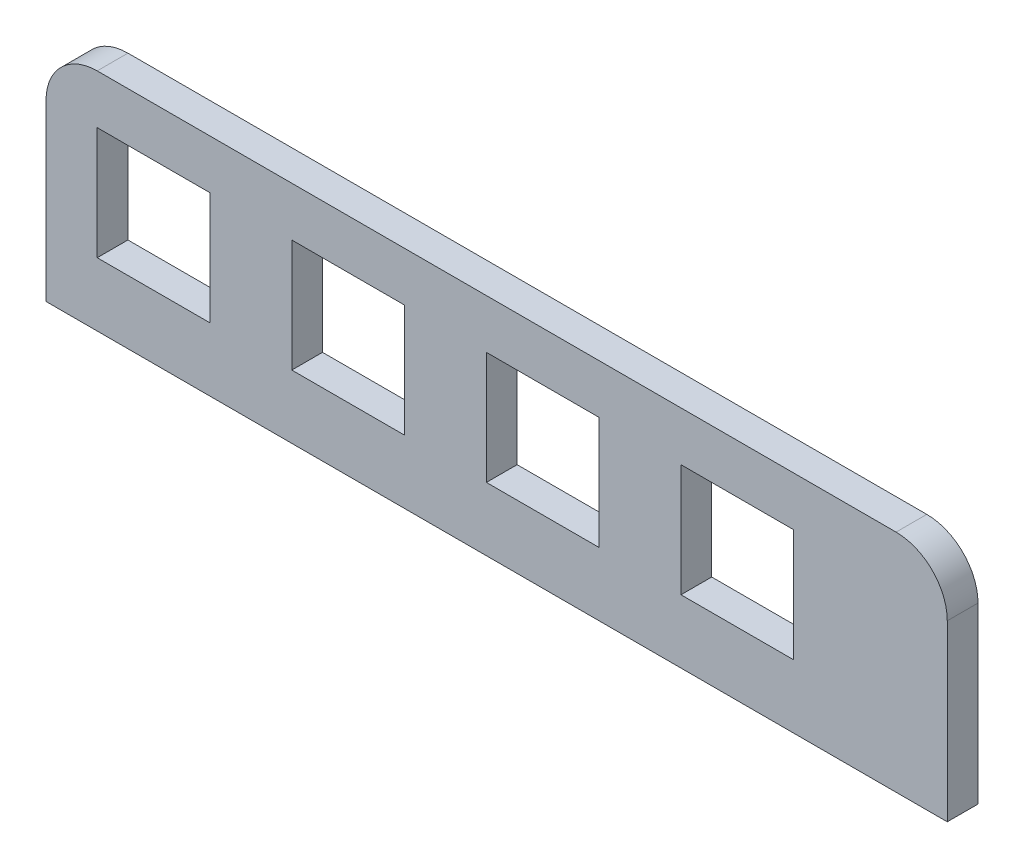
SolidWorks part; units mm, degrees
ref_plane "Front Plane" through (0, 0, 0) normal (0, 0, 1) x (1, 0, 0)
ref_plane "Top Plane" through (0, 0, 0) normal (0, 1, 0) x (1, 0, 0)
ref_plane "Right Plane" through (0, 0, 0) normal (1, 0, 0) x (0, 0, -1)
sketch "Sketch1" plane through (0, 0, 0) normal (0, 0, 1) x (1, 0, 0)
  line L0 (16, 17.2) -> (16, 22) construction
  line L1 (0, 0) -> (88, 0)
  line L2 (0, 0) -> (0, 17)
  line L3 (5, 22) -> (83, 22)
  line L4 (88, 0) -> (88, 17)
  line L5 (5, 6.2) -> (16, 6.2)
  line L6 (5, 6.2) -> (5, 17.2)
  line L7 (5, 17.2) -> (16, 17.2)
  line L8 (16, 6.2) -> (16, 17.2)
  line L10 (16, 6.2) -> (24, 6.2) construction
  line L11 (24, 6.2) -> (35, 6.2)
  line L12 (24, 6.2) -> (24, 17.2)
  line L13 (24, 17.2) -> (35, 17.2)
  line L14 (35, 6.2) -> (35, 17.2)
  line L15 (43, 6.2) -> (54, 6.2)
  line L16 (43, 6.2) -> (43, 17.2)
  line L17 (43, 17.2) -> (54, 17.2)
  line L18 (54, 6.2) -> (54, 17.2)
  line L19 (62, 6.2) -> (73, 6.2)
  line L20 (62, 6.2) -> (62, 17.2)
  line L21 (62, 17.2) -> (73, 17.2)
  line L22 (73, 6.2) -> (73, 17.2)
  line L23 (35, 6.2) -> (43, 6.2) construction
  line L24 (54, 6.2) -> (62, 6.2) construction
  arc A0 (0, 17) -> (5, 22) centre (5, 17) cw
  arc A1 (83, 22) -> (88, 17) centre (83, 17) cw
  point P27 (88, 22)
  dimension "D7" = 5
  dimension "D1" = 15
  dimension "D2" = 22
  dimension "D3" = 11
  dimension "D4" = 11
  dimension "D5" = 5
  dimension "D6" = 8
  dimension "D8" = 6.2
extrude "Boss-Extrude1" add sketch "Sketch1" along normal blind 3
